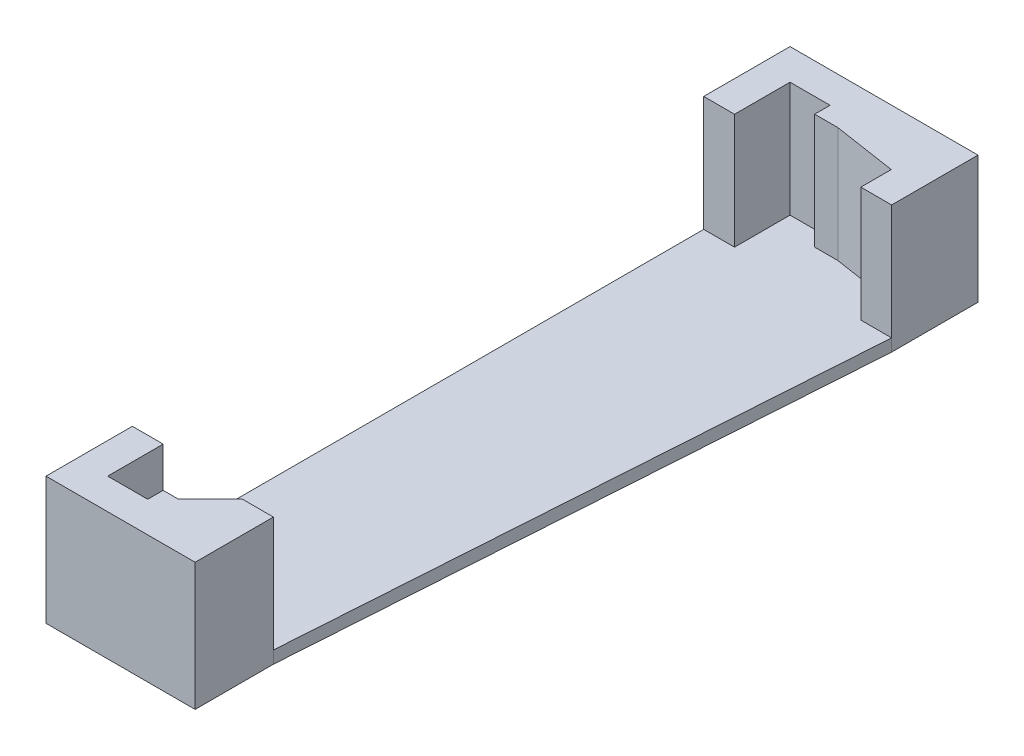
SolidWorks part; units mm, degrees
ref_plane "Front Plane" through (0, 0, 0) normal (0, 0, 1) x (1, 0, 0)
ref_plane "Top Plane" through (0, 0, 0) normal (0, 1, 0) x (1, 0, 0)
ref_plane "Right Plane" through (0, 0, 0) normal (1, 0, 0) x (0, 0, -1)
sketch "Sketch1" plane through (0, 0, 0) normal (0, 1, 0) x (1, 0, 0)
  line L1 (0, 0) -> (38.6999, 0)
  line L2 (0, 0) -> (0, 153.1937)
  line L3 (0, 153.1937) -> (38.6999, 153.1937)
  line L4 (38.6999, 0) -> (38.6999, 153.1937)
  dimension "D1" = 38.6999
  dimension "D2" = 153.1937
extrude "Boss-Extrude1" add sketch "Sketch1" along normal blind 2.54
sketch "Sketch3" plane through (0, 2.54, 0) normal (0, 1, 0) x (1, 0, 0)
  line L0 (6.65, 146.8438) -> (6.35, 146.8438)
  line L1 (6.65, 146.8438) -> (14.5875, 146.8438)
  line L2 (14.5875, 146.8438) -> (14.5875, 143.6687)
  line L3 (14.5875, 143.6687) -> (32.05, 143.6687)
  line L4 (6.35, 146.8438) -> (6.35, 135.4137)
  line L7 (32.05, 143.6687) -> (32.35, 143.6687)
  line L8 (32.35, 143.6687) -> (32.35, 135.4137)
  line L9 (32.35, 135.4137) -> (38.7, 135.4137)
  line L10 (38.7, 135.4137) -> (38.7, 153.1937)
  line L11 (38.7, 153.1937) -> (0, 153.1937)
  line L12 (6.35, 135.4137) -> (0, 135.4137)
  line L13 (0, 153.1937) -> (0, 135.4137)
  line L14 (38.6999, 153.1937) -> (0, 153.1937) construction
  line L15 (0, 153.1937) -> (0, 0) construction
  line L16 (14.5875, 9.525) -> (17.7625, 9.525)
  line L17 (10.6187, 146.8438) -> (10.6187, 76.5969) construction
  line L18 (10.6187, 76.5969) -> (61.4187, 76.5969) construction
  line L19 (30.7032, 0) -> (0, 0)
  line L20 (30.7032, 16.1157) -> (30.7032, 0)
  line L25 (14.5875, 6.35) -> (14.5875, 9.525)
  line L26 (6.65, 6.35) -> (14.5875, 6.35)
  line L27 (6.65, 6.35) -> (6.35, 6.35)
  line L28 (6.35, 6.35) -> (6.35, 17.78)
  line L29 (6.35, 17.78) -> (0, 17.78)
  line L30 (0, 0) -> (0, 17.78)
  line L31 (17.7625, 9.525) -> (24.3532, 16.1157)
  line L32 (24.3532, 16.1157) -> (30.7032, 16.1157)
  line L33 (19.35, 143.6687) -> (32.35, 141.6844)
  point P19 (10.6187, 146.8438)
  dimension "D1" = 17.4625
  dimension "D2" = 7.9375
  dimension "D3" = 3.175
  dimension "D4" = 11.43
  dimension "D5" = 0.3
  dimension "D6" = 0.3
  dimension "D7" = 0
  dimension "D8" = 0
  dimension "D9" = 6.35
  dimension "D10" = 6.35
  dimension "D11" = 6.35
  dimension "D12" = 0
  dimension "D13" = 70.2469
  dimension "D14" = 50.8
  dimension "D15" = 3.175
  dimension "D16" = 135
  dimension "D17" = 6.35
  dimension "D18" = 90
  dimension "D19" = 18.08
  dimension "D20" = 90
  dimension "D21" = 4.7625
  dimension "D22" = 1.9844
extrude "Boss-Extrude2" add sketch "Sketch3" along normal blind 23.7067
sketch "Sketch4" plane through (0, 2.54, 0) normal (0, 1, 0) x (1, 0, 0)
  line L0 (30.7032, 0) -> (38.6999, 0)
  line L1 (38.6999, 0) -> (38.6999, 135.4137)
  line L3 (38.6999, 135.4137) -> (30.7032, 16.1157)
  line L4 (30.7032, 16.1157) -> (30.7032, 0)
  line L5 (38.6999, 0) -> (38.6999, 135.4137) construction
  point P4 (38.6999, 134.5625)
  dimension "D1" = 0
extrude "Cut-Extrude1" cut sketch "Sketch4" against normal through all
